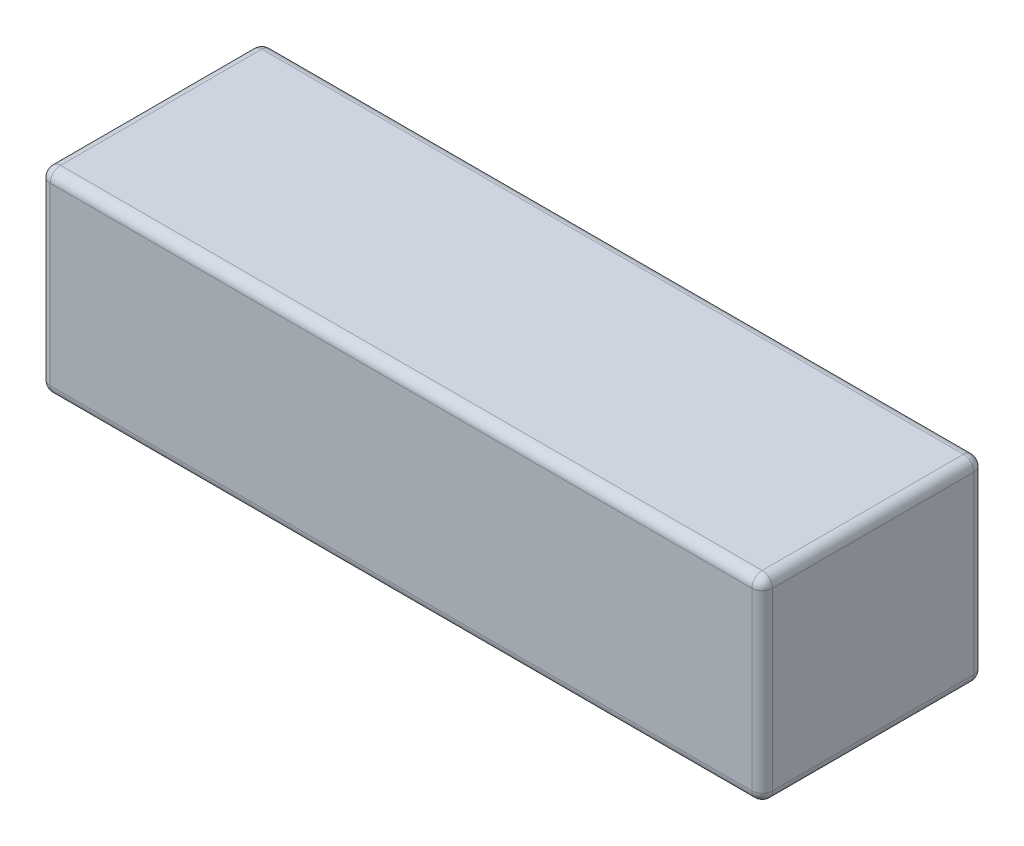
SolidWorks part; units mm, degrees
ref_plane "Płaszczyzna przednia" through (0, 0, 0) normal (0, 0, 1) x (1, 0, 0)
ref_plane "Płaszczyzna górna" through (0, 0, 0) normal (0, 1, 0) x (1, 0, 0)
ref_plane "Płaszczyzna prawa" through (0, 0, 0) normal (1, 0, 0) x (0, 0, -1)
sketch "Szkic1" plane through (0, 0, 0) normal (0, 1, 0) x (1, 0, 0)
  line L1 (-70, -21.5) -> (70, -21.5)
  line L2 (-70, -21.5) -> (-70, 21.5)
  line L3 (-70, 21.5) -> (70, 21.5)
  line L4 (70, -21.5) -> (70, 21.5)
  line L5 (-70, -21.5) -> (70, 21.5) construction
  line L6 (-70, 21.5) -> (70, -21.5) construction
  point P0 (0, 0)
  dimension "D1" = 140
  dimension "D2" = 43
extrude "Dodanie-wyciągnięcie1" add sketch "Szkic1" along normal blind 38
fillet "Zaokrąglenie1" radius 2 12 edges at (0, 38, 21.5) (0, 0, 21.5) (0, 38, -21.5) (0, 0, -21.5) (70, 19, 21.5) (70, 38, 0) (70, 19, -21.5) (70, 0, 0) (-70, 19, -21.5) (-70, 38, 0) (-70, 19, 21.5) (-70, 0, 0)
